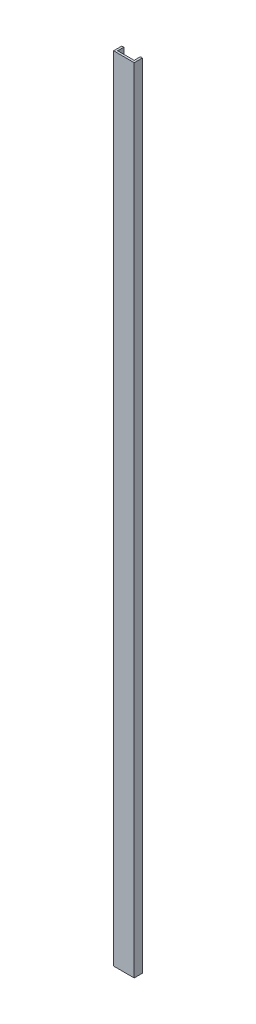
SolidWorks part; units mm, degrees
ref_plane "Front Plane" through (0, 0, 0) normal (0, 0, 1) x (1, 0, 0)
ref_plane "Top Plane" through (0, 0, 0) normal (0, 1, 0) x (1, 0, 0)
ref_plane "Right Plane" through (0, 0, 0) normal (1, 0, 0) x (0, 0, -1)
sketch "Sketch1" plane through (0, 0, 0) normal (0, 1, 0) x (1, 0, 0)
  line L0 (3.175, 3.175) -> (3.175, 12.7)
  line L1 (0, 0) -> (31.75, 0)
  line L2 (0, 0) -> (0, 12.7)
  line L4 (31.75, 0) -> (31.75, 12.7)
  line L5 (3.175, 3.175) -> (28.575, 3.175)
  line L6 (28.575, 3.175) -> (28.575, 12.7)
  line L7 (0, 12.7) -> (3.175, 12.7)
  line L8 (31.75, 12.7) -> (28.575, 12.7)
  dimension "D1" = 31.75
  dimension "D2" = 12.7
  dimension "D3" = 3.175
extrude "Boss-Extrude1" add sketch "Sketch1" along normal blind 1219.2
